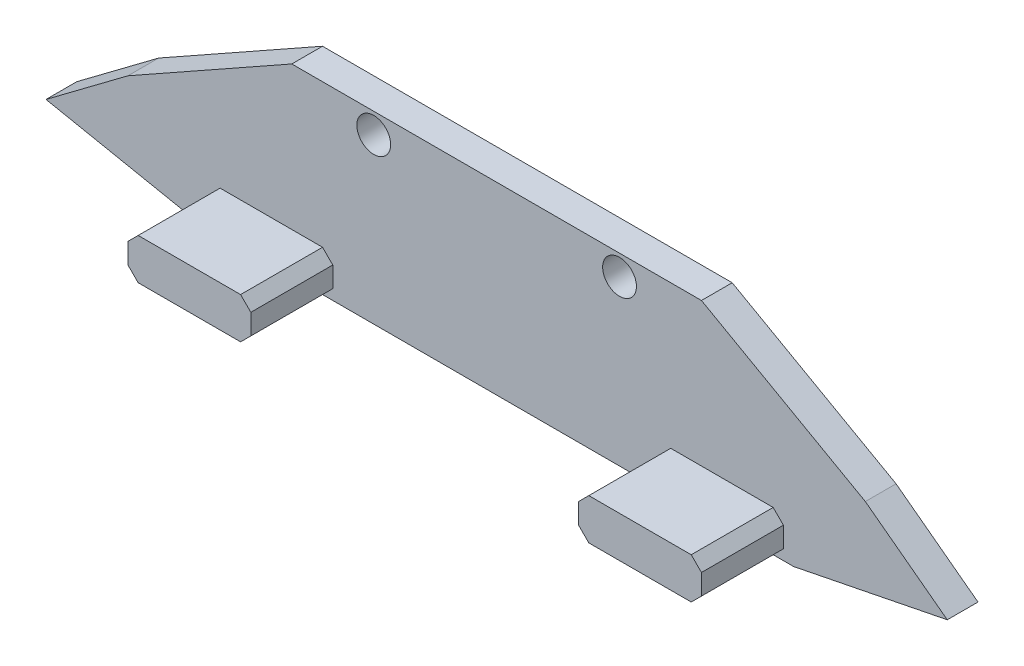
SolidWorks part; units mm, degrees
material "灰色PLA_FDM_原料密度暂定1240"
ref_plane "前视基准面" through (0, 0, 0) normal (0, 0, 1) x (1, 0, 0)
ref_plane "上视基准面" through (0, 0, 0) normal (0, 1, 0) x (1, 0, 0)
ref_plane "右视基准面" through (0, 0, 0) normal (1, 0, 0) x (0, 0, -1)
other "Configuration Table"
sketch "草图1" plane through (0, 0, 0) normal (0, 0, 1) x (1, 0, 0)
  line L0 (-29, 73) -> (29, 73)
  line L1 (29, 73) -> (44, 76)
  line L2 (44, 76) -> (36, 82)
  line L3 (36, 82) -> (20, 91)
  line L4 (20, 91) -> (-20, 91)
  line L5 (-20, 91) -> (-36, 82)
  line L6 (-36, 82) -> (-44, 76)
  line L7 (-44, 76) -> (-29, 73)
  circle A0 centre (-12, 89) radius 1.65
  circle A1 centre (12, 89) radius 1.65
extrude "斜切鼻件底座_3mm" add sketch "草图1" along normal blind 3
sketch "草图2" plane through (0, 0, 0) normal (0, 0, 1) x (1, 0, 0)
  line L0 (-27, 73) -> (-17, 73)
  line L1 (-17, 73) -> (-16, 74)
  line L2 (-16, 74) -> (-16, 76)
  line L3 (-16, 76) -> (-17, 77)
  line L4 (-17, 77) -> (-27, 77)
  line L5 (-27, 77) -> (-28, 76)
  line L6 (-28, 76) -> (-28, 74)
  line L7 (-28, 74) -> (-27, 73)
extrude "低挡块_中央32mm出线口_-1" add sketch "草图2" along normal blind 8 from offset 3
sketch "草图3" plane through (0, 0, 0) normal (0, 0, 1) x (1, 0, 0)
  line L0 (17, 73) -> (27, 73)
  line L1 (27, 73) -> (28, 74)
  line L2 (28, 74) -> (28, 76)
  line L3 (28, 76) -> (27, 77)
  line L4 (27, 77) -> (17, 77)
  line L5 (17, 77) -> (16, 76)
  line L6 (16, 76) -> (16, 74)
  line L7 (16, 74) -> (17, 73)
extrude "低挡块_中央32mm出线口_1" add sketch "草图3" along normal blind 8 from offset 3
